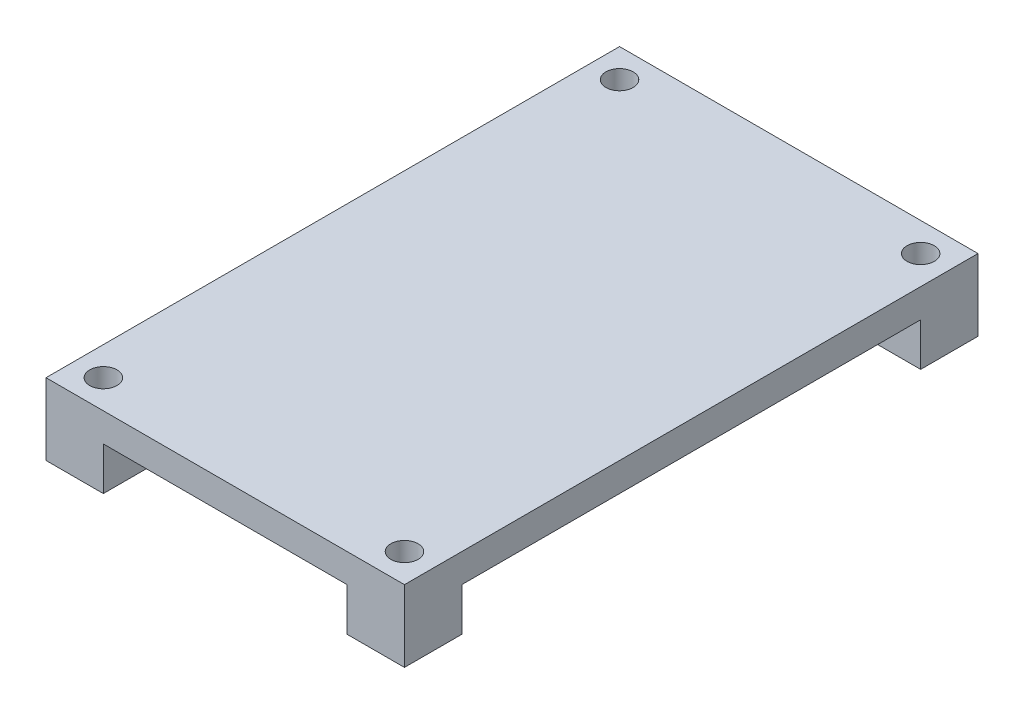
SolidWorks part; units mm, degrees
ref_plane "Front Plane" through (0, 0, 0) normal (0, 0, 1) x (1, 0, 0)
ref_plane "Top Plane" through (0, 0, 0) normal (0, 1, 0) x (1, 0, 0)
ref_plane "Right Plane" through (0, 0, 0) normal (1, 0, 0) x (0, 0, -1)
sketch "Sketch1" plane through (0, 0, 0) normal (0, 1, 0) x (1, 0, 0)
  line L0 (0, 31.2965) -> (0, -31.2965) construction
  line L1 (-12.5, 20) -> (12.5, 20)
  line L2 (-12.5, 20) -> (-12.5, -20)
  line L3 (-12.5, -20) -> (12.5, -20)
  line L4 (12.5, 20) -> (12.5, -20)
  line L5 (-18.7209, 0) -> (18.7209, 0) construction
  circle A0 centre (-10.5, 18) radius 0.95
  circle A1 centre (10.5, 18) radius 0.95
  circle A2 centre (-10.5, -18) radius 0.95
  circle A3 centre (10.5, -18) radius 0.95
  point P11 (0, 0)
  point P12 (-12.5, 0)
  point P13 (0, -20)
  dimension "D5" = 1.9
  dimension "D1" = 25
  dimension "D2" = 40
  dimension "D3" = 2
  dimension "D4" = 2
extrude "Boss-Extrude1" add sketch "Sketch1" along normal blind 2 contours L2 L3 L4 L1
sketch "Sketch2" plane through (0, 0, 0) normal (0, -1, 0) x (-1, 0, 0)
  line L0 (0, 21.434) -> (0, -21.5402) construction
  line L1 (-12.5, 20) -> (-8.5, 20)
  line L2 (-12.5, 20) -> (-12.5, 16)
  line L3 (-12.5, 16) -> (-8.5, 16)
  line L4 (-8.5, 20) -> (-8.5, 16)
  line L5 (-16.8922, 0) -> (16.8922, 0) construction
  line L6 (12.5, 16) -> (8.5, 16)
  line L7 (8.5, 20) -> (8.5, 16)
  line L8 (12.5, 20) -> (8.5, 20)
  line L9 (12.5, 20) -> (12.5, 16)
  line L10 (16.8922, 0) -> (-16.8922, 0) construction
  line L11 (-12.5, -16) -> (-8.5, -16)
  line L12 (-8.5, -20) -> (-8.5, -16)
  line L13 (-12.5, -20) -> (-8.5, -20)
  line L14 (-12.5, -20) -> (-12.5, -16)
  line L15 (12.5, -20) -> (12.5, -16)
  line L16 (12.5, -20) -> (8.5, -20)
  line L17 (8.5, -20) -> (8.5, -16)
  line L18 (12.5, -16) -> (8.5, -16)
  circle A0 centre (-10.5, 18) radius 0.95
  circle A1 centre (-10.5, 18) radius 0.95 construction
  circle A2 centre (10.5, 18) radius 0.95
  circle A3 centre (10.5, -18) radius 0.95
  circle A4 centre (-10.5, -18) radius 0.95
  point P17 (0, 0)
  dimension "D1" = 4
  dimension "D2" = 4
extrude "Boss-Extrude2" add sketch "Sketch2" along normal blind 3
